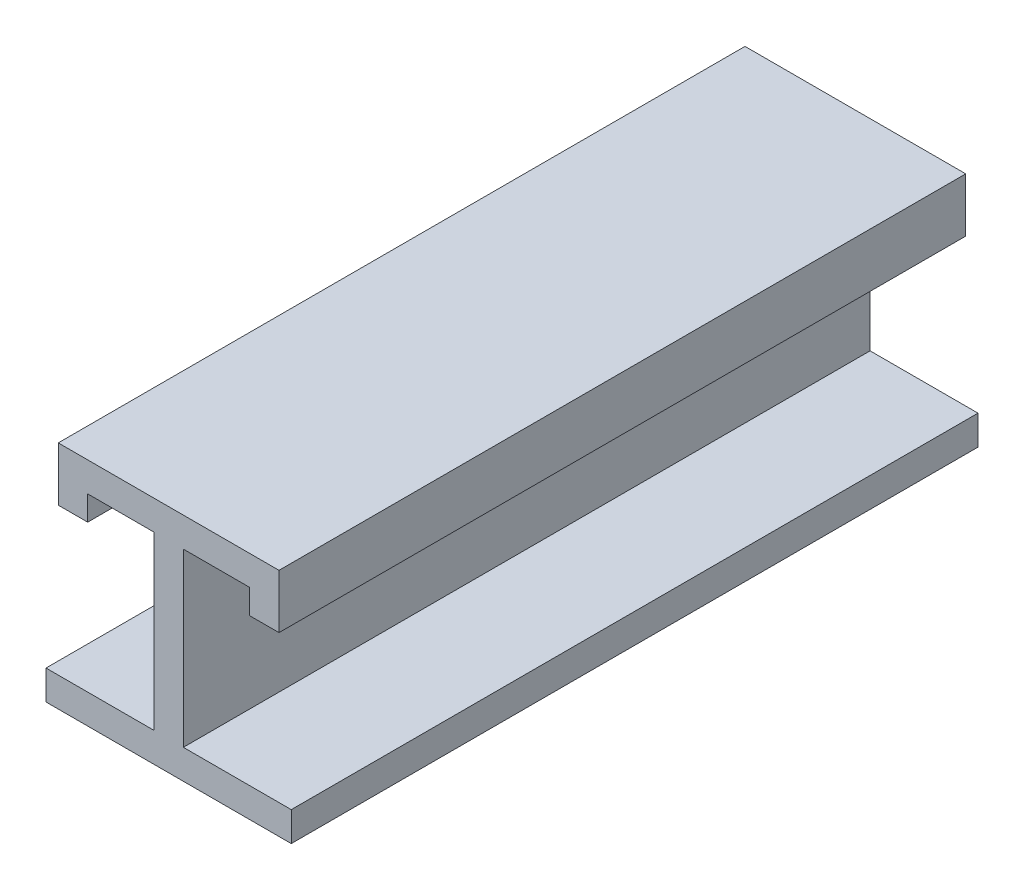
SolidWorks part; units mm, degrees
ref_plane "Спереди" through (0, 0, 0) normal (0, 0, 1) x (1, 0, 0)
ref_plane "Сверху" through (0, 0, 0) normal (0, 1, 0) x (1, 0, 0)
ref_plane "Справа" through (0, 0, 0) normal (1, 0, 0) x (0, 0, -1)
sketch "Эскиз1" plane through (0, 0, 0) normal (0, 0, 1) x (1, 0, 0)
  line L1 (-6, -35) -> (6, -35)
  line L2 (-6, -35) -> (-6, 35)
  line L3 (-6, 35) -> (6, 35)
  line L4 (6, -35) -> (6, 35)
  line L5 (-6, -35) -> (6, 35) construction
  line L6 (-6, 35) -> (6, -35) construction
  line L7 (-50, -47) -> (50, -47)
  line L8 (-50, -47) -> (-50, -35)
  line L9 (-50, -35) -> (50, -35)
  line L10 (50, -47) -> (50, -35)
  line L11 (-50, -47) -> (50, -35) construction
  line L12 (-50, -35) -> (50, -47) construction
  line L13 (-45, 47) -> (45, 47)
  line L14 (-45, 47) -> (-45, 35)
  line L15 (-45, 35) -> (45, 35)
  line L16 (45, 47) -> (45, 35)
  line L17 (-45, 47) -> (45, 35) construction
  line L18 (-45, 35) -> (45, 47) construction
  line L19 (-45, 35) -> (-33, 35)
  line L20 (-45, 35) -> (-45, 25)
  line L21 (-45, 25) -> (-33, 25)
  line L22 (-33, 35) -> (-33, 25)
  line L23 (45, 35) -> (33, 35)
  line L24 (45, 35) -> (45, 25)
  line L25 (45, 25) -> (33, 25)
  line L26 (33, 35) -> (33, 25)
  point P0 (0, 0)
  point P6 (0, -41)
  point P11 (0, 41)
  dimension "D1" = 70
  dimension "D2" = 12
  dimension "D3" = 100
  dimension "D4" = 90
  dimension "D5" = 10
extrude "Бобышка-Вытянуть1" add sketch "Эскиз1" along normal mid plane 280 contours L16 L13 L14 L15 L3 | L1 L4 L3 L2 | L7 L10 L9 L1 L8 | L15 L26 L25 L24 | L22 L15 L20 L21
